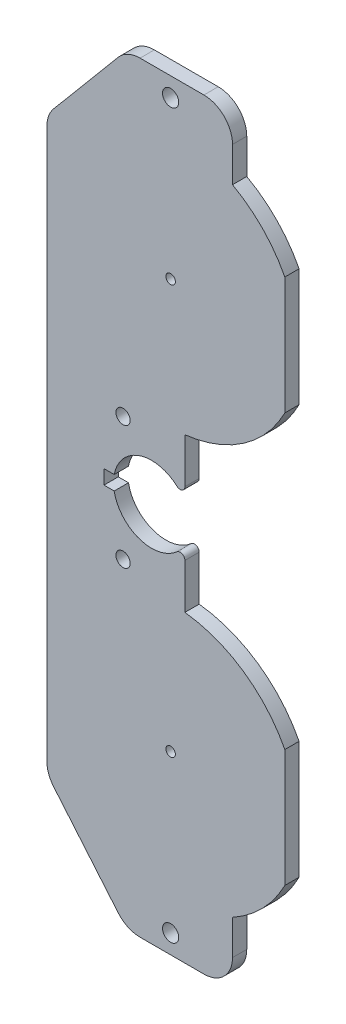
SolidWorks part; units mm, degrees
ref_plane "Спереди" through (0, 0, 0) normal (0, 0, 1) x (1, 0, 0)
ref_plane "Сверху" through (0, 0, 0) normal (0, 1, 0) x (1, 0, 0)
ref_plane "Справа" through (0, 0, 0) normal (1, 0, 0) x (0, 0, -1)
sketch "Эскиз1" plane through (0, 0, 0) normal (0, 0, 1) x (1, 0, 0)
  line L0 (-0.028, -0.014) -> (0.0362, 75.986) construction
  line L1 (-13, 9.0919) -> (-13, 66.9081)
  line L2 (1.5, 36.0635) -> (1.5, 29.9164)
  line L3 (1.5, 39.9365) -> (1.5, 46.0836)
  line L4 (6.5, 4.6678) -> (6.5, 1)
  line L5 (-13, 38) -> (0, 38) construction
  line L6 (12, 53.3153) -> (12, 65.6847)
  line L7 (12, 10.3153) -> (12, 22.6847)
  line L8 (0, 0) -> (0, 76) construction
  line L9 (6.5, 71.3322) -> (6.5, 75)
  line L10 (-3.2101, -2) -> (3.5, -2)
  line L11 (3.5, 78) -> (-3.2101, 78)
  line L12 (-12.2981, 7.1635) -> (-5.5082, -0.9284)
  line L13 (-12.2981, 68.8365) -> (-5.5082, 76.9284)
  line L14 (-5.9291, 37.25) -> (-7, 37.25)
  line L15 (-7, 37.25) -> (-7, 38.75)
  line L16 (-7, 38.75) -> (-5.9291, 38.75)
  circle A0 centre (0, 0) radius 0.85
  circle A1 centre (0, 76) radius 0.85
  arc A2 (6.5, 4.6678) -> (12, 10.3153) centre (0, 16.5) ccw
  arc A3 (12, 65.6847) -> (6.5, 71.3322) centre (0, 59.5) ccw
  arc A4 (1.5, 39.9365) -> (-5.9291, 38.75) centre (-2, 38) ccw
  arc A5 (1.5, 46.0836) -> (12, 53.3153) centre (0, 59.5) ccw
  arc A6 (12, 22.6847) -> (1.5, 29.9164) centre (0, 16.5) ccw
  arc A7 (3.5, -2) -> (6.5, 1) centre (3.5, 1) ccw
  arc A8 (6.5, 75) -> (3.5, 78) centre (3.5, 75) ccw
  circle A9 centre (0, 16.5) radius 0.5
  circle A10 centre (0, 59.5) radius 0.5
  circle A11 centre (-5, 44.5) radius 0.75
  circle A12 centre (-5, 31.5) radius 0.75
  arc A13 (-13, 66.9081) -> (-12.2981, 68.8365) centre (-10, 66.9081) cw
  arc A14 (-13, 9.0919) -> (-12.2981, 7.1635) centre (-10, 9.0919) ccw
  arc A15 (-3.2101, 78) -> (-5.5082, 76.9284) centre (-3.2101, 75) ccw
  arc A16 (-3.2101, -2) -> (-5.5082, -0.9284) centre (-3.2101, 1) cw
  arc A17 (-5.9291, 37.25) -> (1.5, 36.0635) centre (-2, 38) ccw
  point P40 (-13, 68)
  point P43 (-13, 8)
  dimension "D3" = 1.7
  dimension "D7" = 13.5
  dimension "D10" = 4
  dimension "D12" = 3
  dimension "D16" = 1.5
  dimension "D19" = 3
  dimension "D23" = 43
  dimension "D24" = 1
  dimension "D2" = 76
  dimension "D4" = 60
  dimension "D5" = 13
  dimension "D6" = 12
  dimension "D8" = 14.5
  dimension "D9" = 16.5
  dimension "D11" = 11
  dimension "D13" = 80
  dimension "D14" = 6.5
  dimension "D15" = 40
  dimension "D17" = 13
  dimension "D18" = 5
  dimension "D20" = 1.5
  dimension "D21" = 6
  dimension "D22" = 76
extrude "Бобышка-Вытянуть1" add sketch "Эскиз1" along normal blind 1.5
fillet "Скругление1" radius 0.5 2 edges at (1.5, 39.9365, 0.75) (1.5, 36.0635, 0.75)
